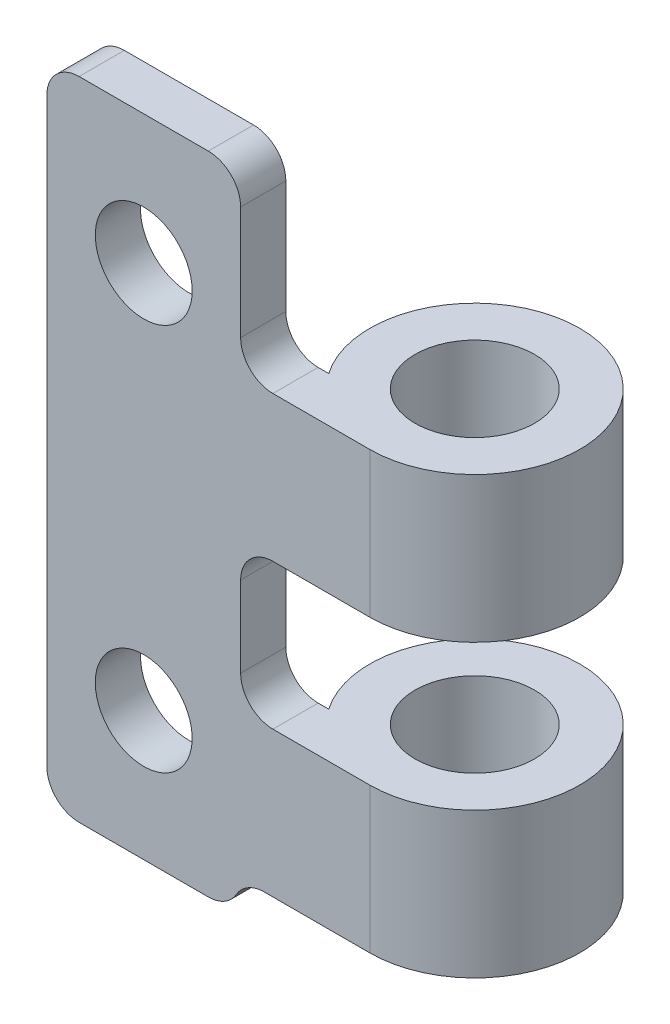
SolidWorks part; units mm, degrees
material "AISI 304"
ref_plane "前视基准面" through (0, 0, 0) normal (0, 0, 1) x (1, 0, 0)
ref_plane "上视基准面" through (0, 0, 0) normal (0, 1, 0) x (1, 0, 0)
ref_plane "右视基准面" through (0, 0, 0) normal (1, 0, 0) x (0, 0, -1)
other "Configuration Table"
sketch "草图1" plane through (0, 0, 0) normal (0, 0, 1) x (1, 0, 0)
  line L0 (-7.4839, 0) -> (6.0532, 0) construction
  line L1 (0, 4.3473) -> (0, -5.8331) construction
  line L3 (-2, -10) -> (2, -10)
  line L4 (-3, -9) -> (-3, 9)
  line L5 (-2, 10) -> (2, 10)
  line L6 (3, -9) -> (3, 9)
  line L7 (-3, -10) -> (3, 10) construction
  line L8 (-3, 10) -> (3, -10) construction
  circle A0 centre (0, 6) radius 1.5
  arc A1 (2, -10) -> (3, -9) centre (2, -9) ccw
  arc A2 (-2, -10) -> (-3, -9) centre (-2, -9) cw
  arc A3 (2, 10) -> (3, 9) centre (2, 9) cw
  arc A4 (-3, 9) -> (-2, 10) centre (-2, 9) cw
  circle A5 centre (0, -6) radius 1.5
  point P4 (0, 0)
  dimension "D1" = 3
  dimension "D4" = 12
  dimension "D5" = 1
  dimension "D2" = 6
  dimension "D3" = 20
extrude "凸台-拉伸1" add sketch "草图1" along normal blind 1.4
ref_plane "基准面1" through (0, -9, 0) normal (0, -1, 0) x (-1, 0, 0)
sketch "草图3" plane through (0, -9, 0) normal (0, -1, 0) x (-1, 0, 0)
  line L0 (-3, -1.4) -> (-2, -1.4) construction
  line L1 (2, -1.4) -> (-2, -1.4) construction
  line L4 (3, -1.4) -> (3, 0) construction
  circle A0 centre (-7, 1.85) radius 3.25 construction
  dimension "D1" = 6.5
  dimension "D2" = 10
sketch "草图4" plane through (0, -9, 0) normal (0, -1, 0) x (-1, 0, 0)
  line L0 (-3, -1.4) -> (-7, -1.4)
  line L1 (-3, 0) -> (-7, 0)
  line L2 (-7, 0) -> (-7, -1.4)
  line L3 (-3, 0) -> (-3, -1.4)
  circle A0 centre (-7, 1.85) radius 3.25 construction
extrude "凸台-拉伸2" add sketch "草图4" against normal blind 4.5
sketch "草图5" plane through (0, -9, 0) normal (0, -1, 0) x (1, 0, 0)
  circle A0 centre (7, -1.85) radius 3.25 construction
  circle A1 centre (7, -1.85) radius 3.25
  circle A2 centre (7, -1.85) radius 1.85
extrude "凸台-拉伸3" add sketch "草图5" against normal up to surface (4.5 mm away) up to face at (5, -4.5, 0.7)
ref_plane "基准面2" through (0, -2.25, 0) normal (0, 1, 0) x (1, 0, 0)
mirror "镜向1" about plane through (0, -2.25, 0) normal (0, 1, 0) of "凸台-拉伸2", "凸台-拉伸3"
fillet "圆角1" radius 1 4 edges at (3, -9, 0.7) (3, 0, 0.7) (3, -4.5, 0.7) (3, 4.5, 0.7)
